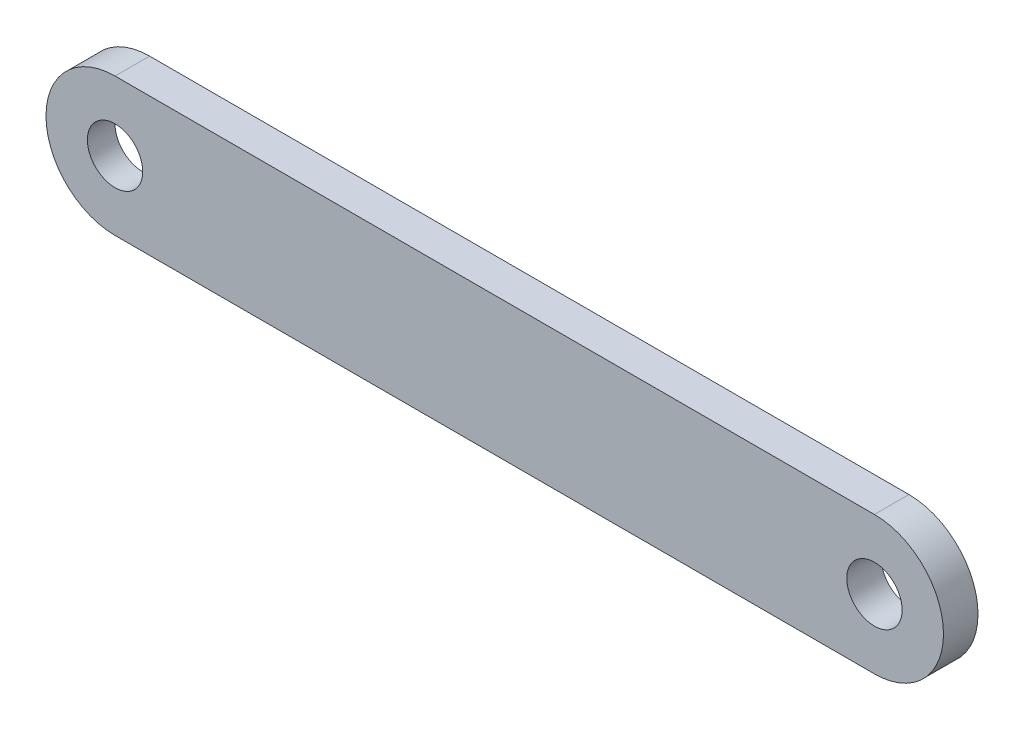
SolidWorks part; units mm, degrees
ref_plane "Front Plane" through (0, 0, 0) normal (0, 0, 1) x (1, 0, 0)
ref_plane "Top Plane" through (0, 0, 0) normal (0, 1, 0) x (1, 0, 0)
ref_plane "Right Plane" through (0, 0, 0) normal (1, 0, 0) x (0, 0, -1)
sketch "Sketch1" plane through (0, 0, 0) normal (0, 0, 1) x (1, 0, 0)
  line L0 (0, 10) -> (110, 10)
  line L1 (0, -10) -> (110, -10)
  circle A0 centre (0, 0) radius 10
  circle A2 centre (0, 0) radius 4.01
  circle A3 centre (110, 0) radius 4.01
  circle A4 centre (110, 0) radius 10
  dimension "D1" = 20
  dimension "D2" = 20
  dimension "D4" = 8.02
  dimension "D5" = 8.02
  dimension "D3" = 110
  dimension "D6" = 110
extrude "Boss-Extrude1" add sketch "Sketch1" along normal blind 5
sketch "Sketch2" plane through (0, 0, 0) normal (0, 0, -1) x (-1, 0, 0)
  circle A2 centre (-20, 0) radius 1.49
  dimension "D1" = 20
  dimension "D2" = 2.98
extrude "Boss-Extrude3" add sketch "Sketch2" along normal blind 4
sketch "Sketch4" plane through (0, 0, 0) normal (0, 0, -1) x (-1, 0, 0)
  line L0 (4.9531, 4.9852) -> (-5.0469, 4.9852)
  line L2 (4.9531, 4.9852) -> (-5.0469, 4.9852)
  line L3 (4.9531, 4.9852) -> (4.9531, 7.4852)
  line L4 (4.9531, 7.4852) -> (-5.0469, 7.4852)
  line L5 (-5.0469, 4.9852) -> (-5.0469, 7.4852)
  dimension "D1" = 2.5
  dimension "D2" = 10
sketch "Sketch5" plane through (0, 0, 0) normal (0, 0, -1) x (-1, 0, 0)
  line L1 (-6.05, -5.05) -> (6.05, -5.05)
  line L2 (-6.05, -5.05) -> (-6.05, 5.05)
  line L3 (-6.05, 5.05) -> (6.05, 5.05)
  line L4 (6.05, -5.05) -> (6.05, 5.05)
  line L5 (-6.05, -5.05) -> (6.05, 5.05) construction
  line L6 (-6.05, 5.05) -> (6.05, -5.05) construction
  point P0 (0, 0)
  dimension "D1" = 12.1
  dimension "D2" = 10.1
extrude "Cut-Extrude1" cut sketch "Sketch5" against normal blind 1
